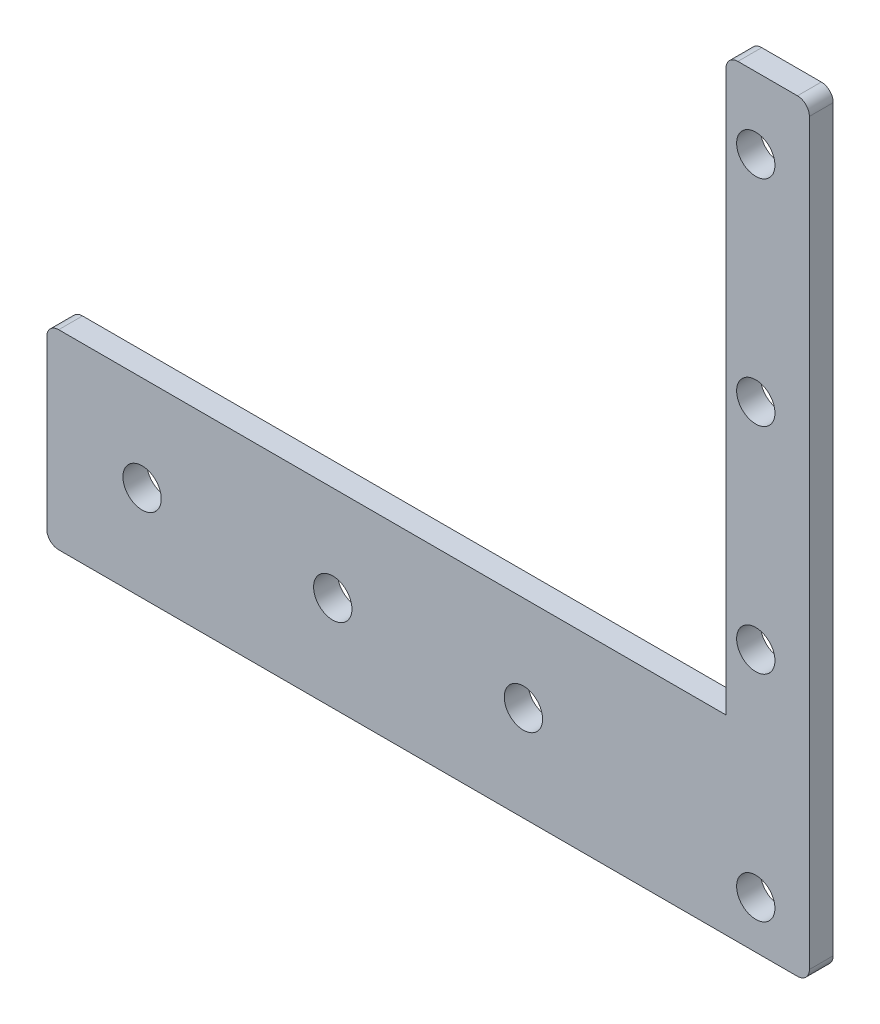
SolidWorks part; units mm, degrees
material "6061 Alloy"
ref_plane "Front" through (0, 0, 0) normal (0, 0, 1) x (1, 0, 0)
ref_plane "Top" through (0, 0, 0) normal (0, 1, 0) x (1, 0, 0)
ref_plane "Right" through (0, 0, 0) normal (1, 0, 0) x (0, 0, -1)
sketch "Sketch1" plane through (0, 0, 0) normal (0, 0, 1) x (1, 0, 0)
  line L0 (0, 0) -> (0, 101.6)
  line L1 (0, 101.6) -> (-11.1125, 101.6)
  line L2 (-11.1125, 101.6) -> (-11.1125, 25.4)
  line L3 (-11.1125, 25.4) -> (-101.6, 25.4)
  line L4 (-101.6, 25.4) -> (-101.6, 0)
  line L5 (-101.6, 0) -> (0, 0)
  dimension "D1" = 25.4
  dimension "D2" = 101.6
  dimension "D3" = 11.1125
  dimension "D4" = 101.6
extrude "Boss-Extrude1" add sketch "Sketch1" along normal blind 3.175
hole_wizard "#10 Clearance Hole1" positions "Sketch2" profile "Sketch3" hole size "#10" standard "ANSI Inch" end condition through all
sketch "Sketch2" plane through (0, 0, 3.175) normal (0, 0, 1) x (1, 0, 0)
  point P0 (-7.1438, 6.35)
  point P3 (-7.1438, 34.925)
  point P6 (-7.1438, 63.5)
  point P9 (-7.1438, 92.075)
sketch "Sketch3" plane through (-7.1438, 6.35, 3.175) normal (1, 0, 0) x (0, -1, 0)
  line L0 (0, 0) -> (0, 3.175)
  line L1 (0, 3.175) -> (2.5527, 3.175)
  line L2 (2.5527, 3.175) -> (2.5527, 0)
  line L5 (2.5527, 0) -> (0, 0)
  line L11 (0, -6.35) -> (0, 107.95) construction
  dimension "Thru Hole Dia." = 5.1054
  dimension "Thru Hole Depth" = 3.175
hole_wizard "#10 Clearance Hole2" positions "Sketch4" profile "Sketch5" hole size "#10" standard "ANSI Inch" end condition through all
sketch "Sketch4" plane through (0, 0, 3.175) normal (0, 0, 1) x (1, 0, 0)
  line L0 (-101.6, 12.7) -> (0, 12.7) construction
  line L1 (-101.6, 25.4) -> (-101.6, 0) construction
  line L2 (0, 0) -> (0, 101.6) construction
  point P8 (-38.1, 12.7)
  point P10 (-63.5, 12.7)
  point P12 (-88.9, 12.7)
  dimension "D1" = 38.1
  dimension "D2" = 25.4
  dimension "D3" = 25.4
sketch "Sketch5" plane through (-88.9, 12.7, 3.175) normal (1, 0, 0) x (0, -1, 0)
  line L0 (0, 0) -> (0, 3.175)
  line L1 (0, 3.175) -> (2.5527, 3.175)
  line L2 (2.5527, 3.175) -> (2.5527, 0)
  line L5 (2.5527, 0) -> (0, 0)
  line L11 (0, -6.35) -> (0, 107.95) construction
  dimension "Thru Hole Dia." = 5.1054
  dimension "Thru Hole Depth" = 3.175
fillet "Fillet1" radius 1.5875 5 edges at (-11.1125, 101.6, 1.5875) (0, 101.6, 1.5875) (0, 0, 1.5875) (-101.6, 0, 1.5875) (-101.6, 25.4, 1.5875)
